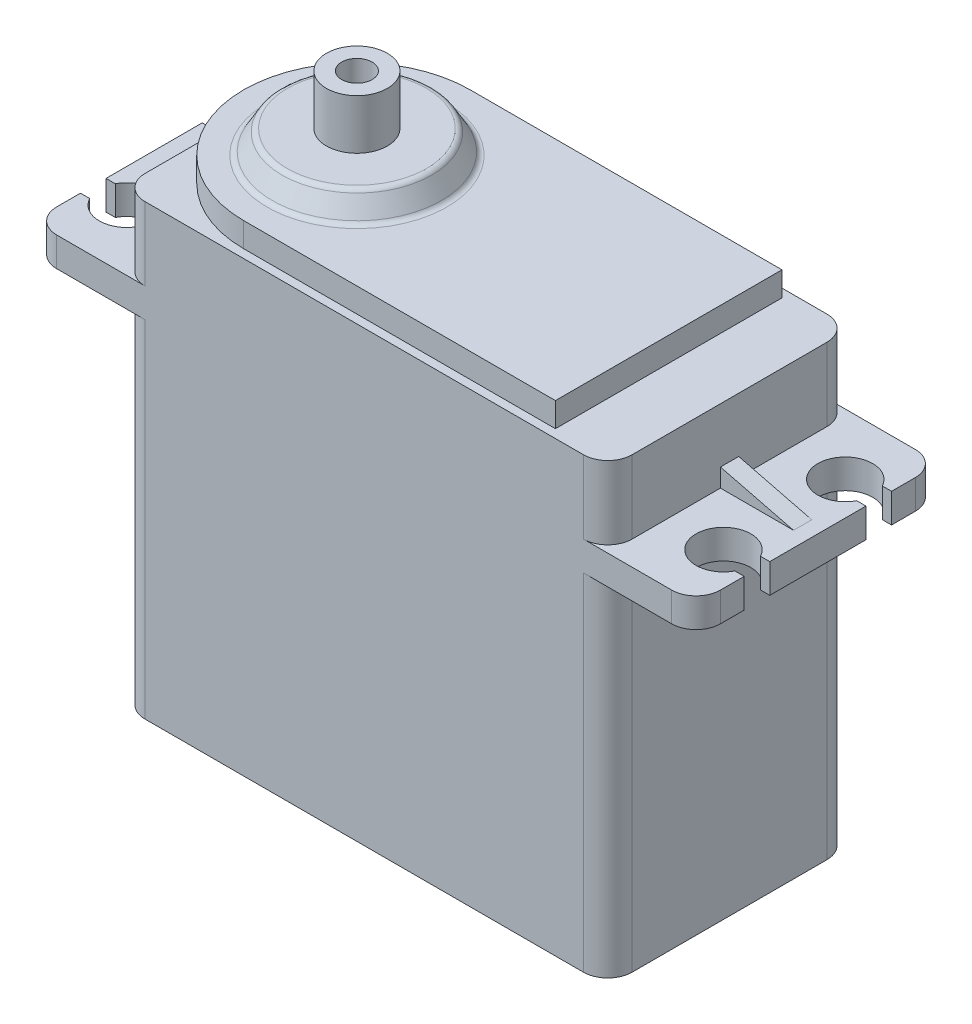
SolidWorks part; units mm, degrees
ref_plane "前视基准面" through (0, 0, 0) normal (0, 0, 1) x (1, 0, 0)
ref_plane "上视基准面" through (0, 0, 0) normal (0, 1, 0) x (1, 0, 0)
ref_plane "右视基准面" through (0, 0, 0) normal (1, 0, 0) x (0, 0, -1)
sketch "草图3" plane through (0, 0, 0) normal (0, 0, 1) x (1, 0, 0)
  line L0 (-20, 0) -> (20, 0)
  line L1 (20, 0) -> (20, 35.1)
  line L2 (-20, 0) -> (-20, 34.4)
  line L4 (-13.8, 38.8) -> (16, 38.8)
  line L5 (16, 38.8) -> (20, 38.8)
  line L6 (20, 38.8) -> (20, 35.1)
  line L7 (-13.8, 38.8) -> (-20, 38.8)
  line L8 (-20, 38.8) -> (-20, 34.4)
  dimension "D1" = 38.8
  dimension "D2" = 40
  dimension "D3" = 6.2
  dimension "D4" = 4.4
  dimension "D5" = 3.7
  dimension "D6" = 4
  dimension "D7" = 0
  dimension "D8" = 20
extrude "凸台-拉伸1" add sketch "草图3" along normal mid plane 20
sketch "草图4" plane through (0, 0, 0) normal (0, 1, 0) x (1, 0, 0)
  line L1 (-27.25, 10) -> (27.25, 10)
  line L2 (-27.25, 10) -> (-27.25, -10)
  line L3 (-27.25, -10) -> (27.25, -10)
  line L4 (27.25, 10) -> (27.25, -10)
  line L5 (-27.25, 10) -> (27.25, -10) construction
  line L6 (-27.25, -10) -> (27.25, 10) construction
  point P0 (0, 0)
  dimension "D1" = 20
  dimension "D2" = 54.5
extrude "凸台-拉伸2" add sketch "草图4" against normal blind 2.4 from offset 30.8
sketch "草图5" plane through (0, 30.8, 0) normal (0, 1, 0) x (1, 0, 0)
  line L0 (0, 0) -> (9.3248, 0) construction
  line L1 (-24.5, 5) -> (24.5, 5)
  line L2 (-24.5, 5) -> (-24.5, -5)
  line L3 (-24.5, -5) -> (24.5, -5)
  line L4 (24.5, 5) -> (24.5, -5)
  line L5 (-24.5, 5) -> (24.5, -5) construction
  line L6 (-24.5, -5) -> (24.5, 5) construction
  line L7 (0, 0) -> (0, 7.474) construction
  circle A0 centre (-24.5, 5) radius 2.25
  circle A1 centre (24.5, 5) radius 2.25
  circle A2 centre (24.5, -5) radius 2.25
  circle A3 centre (-24.5, -5) radius 2.25
  point P0 (0, 0)
  dimension "D3" = 4.5
  dimension "D1" = 49
  dimension "D2" = 10
extrude "切除-拉伸1" cut sketch "草图5" against normal blind 3.1 contours A0 | A1 | A2 | A3
sketch "草图6" plane through (0, 30.8, 0) normal (0, 1, 0) x (1, 0, 0)
  line L0 (-27.25, 10) -> (-27.25, -10) construction
  line L1 (-25.25, 6.05) -> (-27.25, 6.05)
  line L2 (-25.25, 6.05) -> (-25.25, 3.95)
  line L3 (-25.25, 3.95) -> (-27.25, 3.95)
  line L4 (-27.25, 6.05) -> (-27.25, 3.95)
  line L5 (-25.25, 6.05) -> (-27.25, 3.95) construction
  line L6 (-25.25, 3.95) -> (-27.25, 6.05) construction
  line L7 (0, 0) -> (6.6987, 0) construction
  line L8 (0, 0) -> (0, 7.3087) construction
  line L9 (27.25, 6.05) -> (27.25, 3.95)
  line L10 (25.25, 3.95) -> (27.25, 3.95)
  line L11 (25.25, 6.05) -> (25.25, 3.95)
  line L12 (25.25, 6.05) -> (27.25, 6.05)
  line L13 (25.25, -6.05) -> (27.25, -6.05)
  line L14 (25.25, -6.05) -> (25.25, -3.95)
  line L15 (25.25, -3.95) -> (27.25, -3.95)
  line L16 (27.25, -6.05) -> (27.25, -3.95)
  line L17 (-27.25, -6.05) -> (-27.25, -3.95)
  line L18 (-25.25, -3.95) -> (-27.25, -3.95)
  line L19 (-25.25, -6.05) -> (-25.25, -3.95)
  line L20 (-25.25, -6.05) -> (-27.25, -6.05)
  circle A0 centre (-24.5, 5) radius 2.25 construction
  point P0 (-26.25, 5)
  point P12 (26.25, 5)
  point P18 (26.25, -5)
  point P19 (-26.25, -5)
  dimension "D1" = 0
  dimension "D2" = 2.1
  dimension "D3" = 2
extrude "切除-拉伸2" cut sketch "草图6" against normal blind 3.1
sketch "草图7" plane through (0, 0, 0) normal (0, 0, 1) x (1, 0, 0)
  line L0 (-13.8716, 40.7) -> (3.5848, 40.7)
  line L1 (-20, 0) -> (20, 0) construction
  dimension "D1" = 40.7
surface "曲面-拉伸1" sketch "草图7" parameters "D1"=3.1
sketch "草图8" plane through (0, 40.7, 0) normal (0, -1, 0) x (1, 0, 0)
  circle A0 centre (-10.6, 0) radius 6
  dimension "D1" = 12
  dimension "D3" = 10.6
  dimension "D2" = 0
extrude "凸台-拉伸3" add sketch "草图8" along normal up to body (1.9 mm away) draft 30 separate body
sketch "草图9" plane through (0, 40.7, 0) normal (0, 1, 0) x (1, 0, 0)
  circle A0 centre (-10.6, 0) radius 2.5
  dimension "D1" = 5
extrude "凸台-拉伸4" add sketch "草图9" along normal blind 4.1
sketch "草图10" plane through (0, 44.8, 0) normal (0, 1, 0) x (1, 0, 0)
  circle A0 centre (-10.6, 0) radius 1.25
  dimension "D1" = 2.5
extrude "切除-拉伸3" cut sketch "草图10" against normal blind 9
cosmetic thread "装饰螺纹线1" parameters "D2"=3
sketch "草图11" plane through (0, 0, 0) normal (0, 0, 1) x (1, 0, 0)
  line L0 (-20, 32.3) -> (-26, 30.8)
  line L3 (-26, 30.8) -> (-20, 30.8)
  line L4 (-20, 30.8) -> (-20, 32.3)
  line L5 (0, 0) -> (0, 21.1422) construction
  line L6 (20, 30.8) -> (20, 32.3)
  line L7 (26, 30.8) -> (20, 30.8)
  line L8 (20, 32.3) -> (26, 30.8)
  dimension "D1" = 1.5
  dimension "D2" = 6
extrude "凸台-拉伸5" add sketch "草图11" along normal mid plane 1.5
sketch "草图12" plane through (0, 38.8, 0) normal (0, 1, 0) x (1, 0, 0)
  line L0 (-10.6, 9.3) -> (15, 9.3)
  line L1 (15, 9.3) -> (15, -9.3)
  line L2 (15, -9.3) -> (-10.6, -9.3)
  line L4 (20, -10) -> (20, 10) construction
  line L6 (-20, 10) -> (20, 10)
  line L7 (-20, 10) -> (-20, -10)
  line L8 (-20, -10) -> (20, -10)
  line L9 (20, 10) -> (20, -10)
  arc A0 (-10.6, -9.3) -> (-10.6, 9.3) centre (-10.6, 0) cw
  dimension "D2" = 9.3
  dimension "D1" = 5
extrude "切除-拉伸5" cut sketch "草图12" against normal blind 2
fillet "圆角1" radius 2 12 edges at (20, 14.2, 10) (-20, 33.8, -10) (-20, 33.8, 10) (-20, 14.2, -10) (20, 33.8, -10) (-20, 14.2, 10) (20, 33.8, 10) (27.25, 29.6, 10) (-27.25, 29.6, -10) (27.25, 29.6, -10) (-27.25, 29.6, 10) (20, 14.2, -10)
fillet "圆角2" radius 0.5 2 edges at (-10.6, 40.7, -6) (-10.6, 38.8, -7.097)
